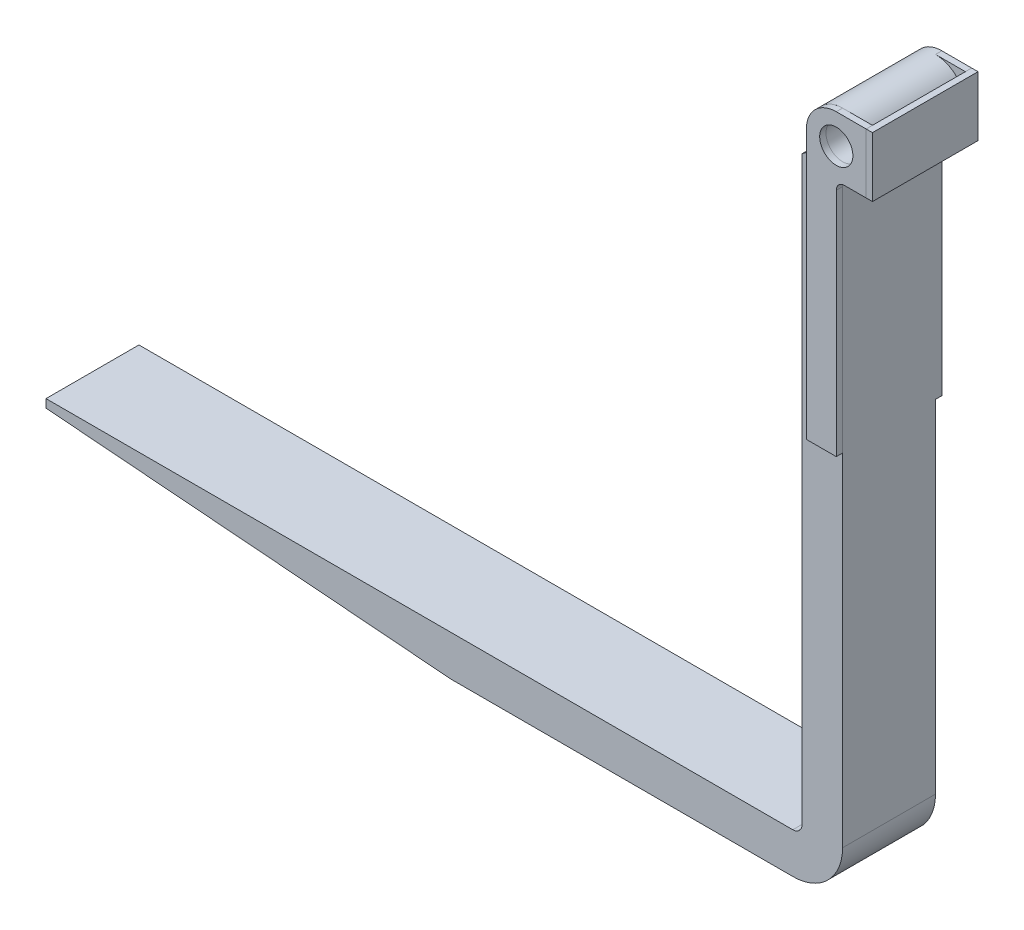
SolidWorks part; units mm, degrees
ref_plane "Front Plane" through (0, 0, 0) normal (0, 0, 1) x (1, 0, 0)
ref_plane "Top Plane" through (0, 0, 0) normal (0, 1, 0) x (1, 0, 0)
ref_plane "Right Plane" through (0, 0, 0) normal (1, 0, 0) x (0, 0, -1)
sketch "Sketch1" plane through (0, 0, 0) normal (0, 0, 1) x (1, 0, 0)
  line L0 (0, 75) -> (0, 950)
  line L1 (-75, 0) -> (-1200, 0)
  arc A0 (0, 75) -> (-75, 0) centre (-75, 75) cw
  point P6 (0, 0)
  dimension "D3" = 75
  dimension "D1" = 1200
  dimension "D2" = 950
extrude "Extrude-Thin1" add sketch "Sketch1" along normal mid plane 140 thin thin type one direction wall 61
sketch "Sketch2" plane through (0, 0, 70) normal (0, 0, 1) x (1, 0, 0)
  line L0 (-1200, 48.5) -> (-590, 0)
  line L1 (-1200, 0) -> (-1200, 61) construction
  line L2 (-75, 0) -> (-1200, 0) construction
  point P6 (0, 0)
  dimension "D1" = 12.5
  dimension "D2" = 610
extrude "Cut-Extrude2" cut sketch "Sketch2" against normal through all both and the other way through all flip side to cut
sketch "Sketch3" plane through (0, 0, 0) normal (0, 0, 1) x (1, 0, 0)
  line L0 (0, 950) -> (0, 995) construction
  circle A0 centre (0, 995) radius 45
  circle A1 centre (0, 995) radius 25
  dimension "D1" = 50
  dimension "D2" = 90
extrude "Boss-Extrude1" add sketch "Sketch3" along normal mid plane 140 separate body
sketch "Sketch4" plane through (0, 0, 0) normal (0, 0, 1) x (1, 0, 0)
  line L0 (-61, 950) -> (0, 950) construction
  line L1 (-61, 950) -> (0, 950)
  line L2 (-61, 950) -> (-35.7327, 968.6398)
  circle A0 centre (0, 995) radius 45 construction
  circle A1 centre (0, 995) radius 45
extrude "Boss-Extrude2" add sketch "Sketch4" along normal mid plane 140 separate body contours A1 L2 L1
sketch "Sketch5" plane through (0, 0, 70) normal (0, 0, 1) x (1, 0, 0)
  line L0 (-45, 995) -> (-45, 590)
  line L1 (-45, 590) -> (0, 590)
  line L2 (0, 950) -> (0, 75) construction
  line L3 (0, 590) -> (0, 937.5)
  line L4 (12.5, 950) -> (45, 950)
  line L5 (45, 950) -> (45, 1040)
  line L6 (45, 1040) -> (0, 1040)
  circle A0 centre (0, 995) radius 45 construction
  arc A1 (0, 1040) -> (-45, 995) centre (0, 995) ccw
  arc A2 (0, 937.5) -> (12.5, 950) centre (12.5, 937.5) cw
  point P17 (0, 950)
  circle M9 centre (0, 995) radius 45
  circle M10 centre (0, 995) radius 25
  dimension "D1" = 12.5
  dimension "D2" = 450
extrude "Boss-Extrude3" add sketch "Sketch5" along normal blind 9.5 separate body contours M9 M10 | L5 L6 M9 | L3 A2 L4 L5 L0 L1 M9
mirror "Mirror2" about plane through (0, 0, 0) normal (0, 0, 1) of "Boss-Extrude3"
sketch "Sketch6" plane through (45, 0, 0) normal (1, 0, 0) x (0, 0, -1)
  line L1 (-79.5, 950) -> (79.5, 950)
  line L2 (-79.5, 950) -> (-79.5, 1040)
  line L3 (-79.5, 1040) -> (79.5, 1040)
  line L4 (79.5, 950) -> (79.5, 1040)
extrude "Boss-Extrude4" add sketch "Sketch6" along normal blind 9.5 separate body
